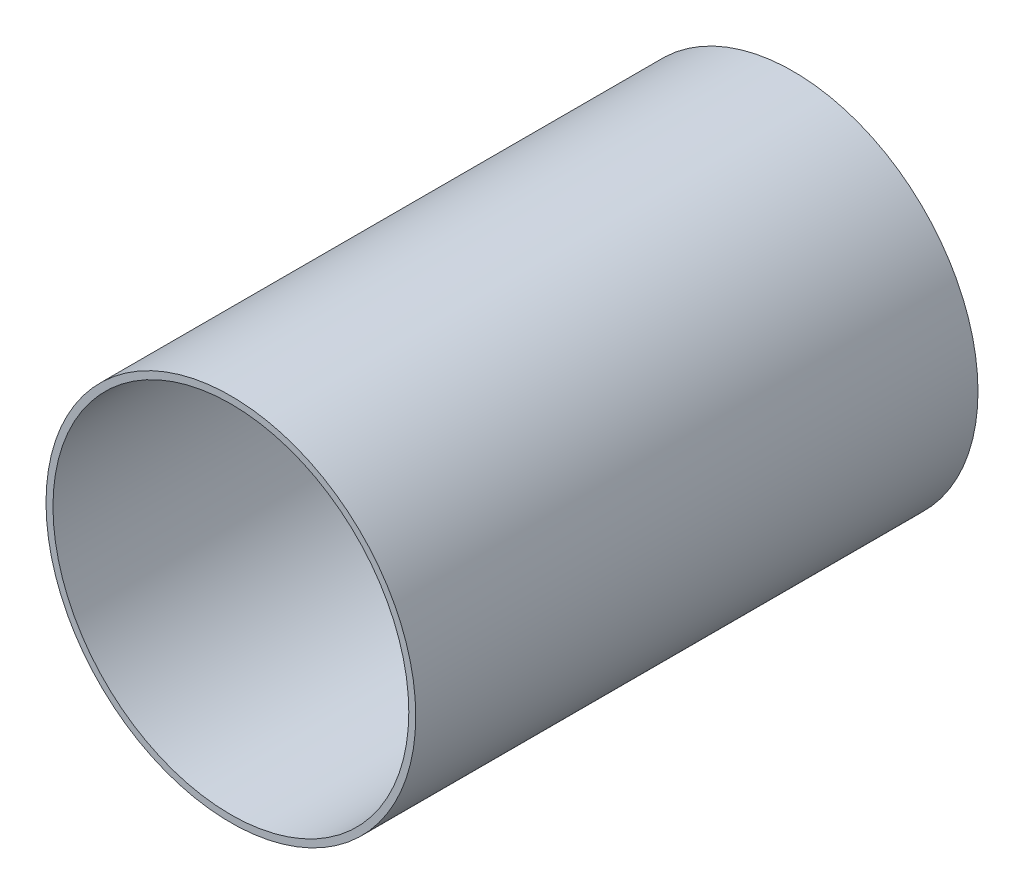
SolidWorks part; units mm, degrees
material "Thornel Mat VMA"
ref_plane "Front Plane" through (0, 0, 0) normal (0, 0, 1) x (1, 0, 0)
ref_plane "Top Plane" through (0, 0, 0) normal (0, 1, 0) x (1, 0, 0)
ref_plane "Right Plane" through (0, 0, 0) normal (1, 0, 0) x (0, 0, -1)
sketch "Sketch1" plane through (0, 0, 0) normal (0, 0, 1) x (1, 0, 0)
  circle A0 centre (0, 0) radius 49.4855
  circle A1 centre (0, 0) radius 47.625
  dimension "D1" = 98.9711
  dimension "D2" = 95.25
extrude "Boss-Extrude1" add sketch "Sketch1" along normal blind 150.495
